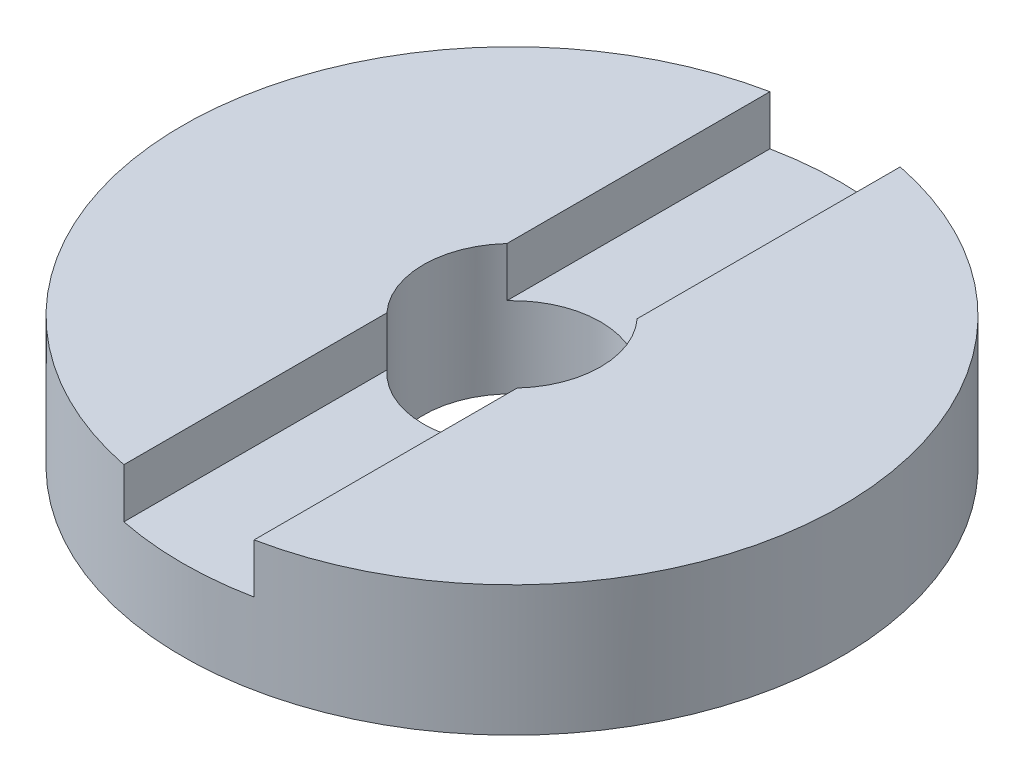
SolidWorks part; units mm, degrees
ref_plane "Plan de face" through (0, 0, 0) normal (0, 0, 1) x (1, 0, 0)
ref_plane "Plan de dessus" through (0, 0, 0) normal (0, 1, 0) x (1, 0, 0)
ref_plane "Plan de droite" through (0, 0, 0) normal (1, 0, 0) x (0, 0, -1)
sketch "Esquisse1" plane through (0, 0, 0) normal (0, 0, 1) x (1, 0, 0)
  line L0 (0, 0) -> (0, 27.945) construction
  line L1 (-2.5, 0) -> (-12.65, 0)
  line L2 (-12.65, 0) -> (-12.65, 5)
  line L3 (-12.65, 5) -> (-2.5, 5)
  line L5 (-2.5, 5) -> (-2.5, 0)
  dimension "D1" = 25.3
  dimension "D2" = 5
  dimension "D3" = 5
revolve "Révolution1" add sketch "Esquisse1" angle 360 about L0
sketch "Esquisse2" plane through (0, 5, 0) normal (0, 1, 0) x (1, 0, 0)
  line L2 (-2.5, 12.4005) -> (-2.5, -12.4005)
  line L4 (2.5, 12.4005) -> (2.5, -12.4005)
  circle A0 centre (0, 0) radius 12.65 construction
  arc A1 (-2.5, -12.4005) -> (2.5, -12.4005) centre (0, 0) ccw
  arc A2 (2.5, 12.4005) -> (-2.5, 12.4005) centre (0, 0) ccw
  dimension "D1" = 5
  dimension "D2" = 2.5
extrude "Enlèv. mat.-Extru.1" cut sketch "Esquisse2" against normal blind 1.9
hole_wizard "Trou taraudé M81" positions "Esquisse4" profile "Esquisse5" tap size "M8" standard "ISO"
sketch "Esquisse4" plane through (0, 0, 0) normal (0, -1, 0) x (1, 0, 0)
  point P0 (0, 0)
sketch "Esquisse5" plane through (0, 0, 0) normal (1, 0, 0) x (0, 0, -1)
  line L0 (0, 0) -> (0, 24.2929)
  line L1 (0, 24.2929) -> (3.4, 22.25)
  line L2 (3.4, 22.25) -> (3.4, 0)
  line L5 (3.4, 0) -> (0, 0)
  line L10 (0, 24.2929) -> (-3.4, 22.25) construction
  line L11 (0, -6.35) -> (0, 107.95) construction
  dimension "Diamètre du trou pour taraudage" = 6.8
  dimension "Profondeur du trou pour taraudage" = 22.25
  dimension "Angle de pointe" = 118
cosmetic thread "Filetage de perçage1" parameters "D1"=5, "D2"=8
